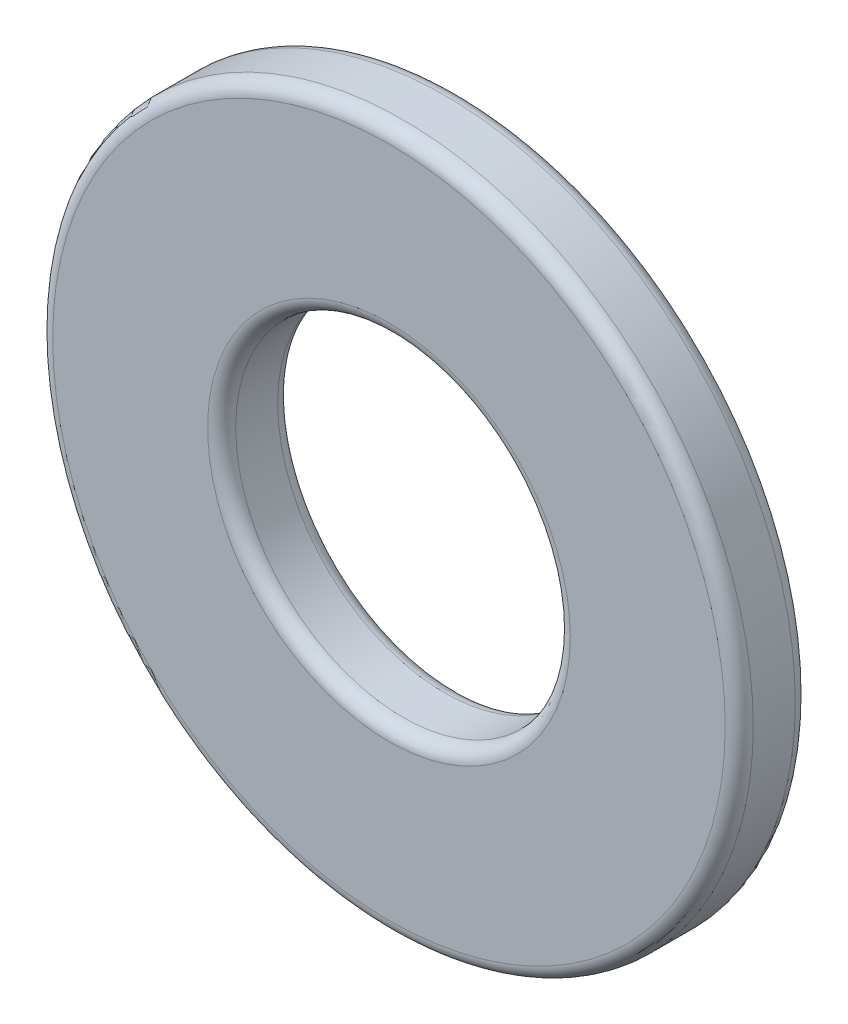
SolidWorks part; units mm, degrees
ref_plane "Front Plane" through (0, 0, 0) normal (0, 0, 1) x (1, 0, 0)
ref_plane "Top Plane" through (0, 0, 0) normal (0, 1, 0) x (1, 0, 0)
ref_plane "Right Plane" through (0, 0, 0) normal (1, 0, 0) x (0, 0, -1)
sketch "Sketch1" plane through (0, 0, 0) normal (0, 0, 1) x (1, 0, 0)
  circle A0 centre (0, 0) radius 4.5 construction
  circle A1 centre (0, 0) radius 2.15 construction
  point P5 (0, -4.5)
  dimension "OD" = 9
  dimension "ID" = 4.3
sketch "Sketch2" plane through (0, 0, 0) normal (1, 0, 0) x (0, 0, -1)
  line L0 (0.35, 0) -> (-0.35, 0) construction
  line L1 (-0.45, -4.5) -> (0.45, -4.5) construction
  point P0 (-0.45, -4.5)
  point P3 (0.45, -4.5)
  point P4 (0, 0)
  point P9 (0, -4.5)
  point P10 (0.35, -4.5)
  point P11 (-0.45, -4.5)
  point P12 (-0.35, -4.5)
  point P13 (0.45, -4.5)
  dimension "Thickness Range [Min]" = 0.7
  dimension "Thickness Range [Max]" = 0.9
sketch "Sketch3" plane through (0, 0, 0) normal (0, 0, 1) x (1, 0, 0)
  circle A0 centre (0, 0) radius 2.15 construction
  circle A1 centre (0, 0) radius 4.5 construction
  circle A2 centre (0, 0) radius 2.15
  circle A3 centre (0, 0) radius 4.5
extrude "Boss-Extrude1" add sketch "Sketch3" against normal up to vertex (0.45 mm away) and the other way up to vertex (0.45 mm away) up to point (0, -4.5, -0.45) other way up to point (0, -4.5, 0.45)
fillet "Fillet1" radius 0.18 4 edges at (4.5, 0, -0.45) (2.15, 0, -0.45) (2.15, 0, 0.45) (4.5, 0, 0.45)
equation "\"D1@Fillet1\"=\"OD@Sketch1\"*.02"
